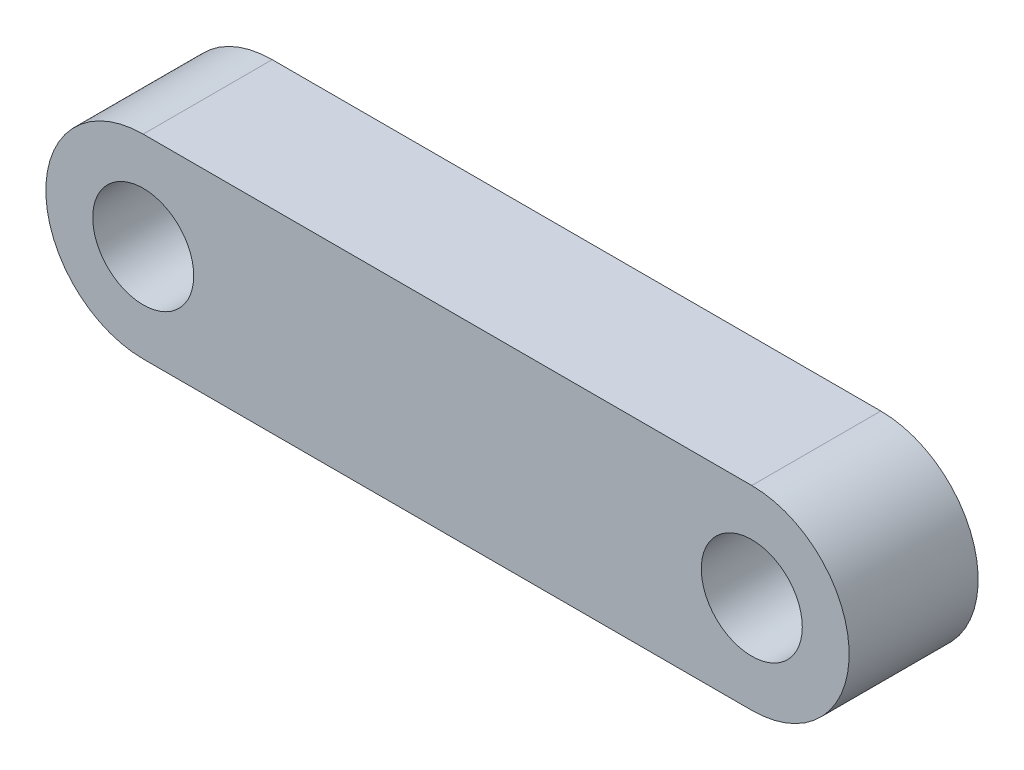
SolidWorks part; units mm, degrees
material "ABS"
ref_plane "Front Plane" through (0, 0, 0) normal (0, 0, 1) x (1, 0, 0)
ref_plane "Top Plane" through (0, 0, 0) normal (0, 1, 0) x (1, 0, 0)
ref_plane "Right Plane" through (0, 0, 0) normal (1, 0, 0) x (0, 0, -1)
sketch "Sketch1" plane through (0, 0, 0) normal (0, 0, 1) x (1, 0, 0)
  line L0 (0, 27.2364) -> (0, -32.7408) construction
  line L1 (25, -36.3) -> (-25, -36.3)
  line L2 (-30.9956, -23.0035) -> (-5.9956, 5.2965)
  line L3 (30.9956, -23.0035) -> (5.9956, 5.2965)
  line L4 (-25, -20.3) -> (25, -20.3)
  circle A0 centre (0, 0) radius 4
  circle A1 centre (0, 0) radius 11 construction
  circle A2 centre (-25, -28.3) radius 4.15
  arc A3 (-25, -36.3) -> (-30.9956, -23.0035) centre (-25, -28.3) cw
  arc A4 (-5.9956, 5.2965) -> (5.9956, 5.2965) centre (0, 0) cw
  arc A5 (25, -36.3) -> (30.9956, -23.0035) centre (25, -28.3) ccw
  circle A6 centre (25, -28.3) radius 4.15
  arc A7 (-25, -20.3) -> (-30.9956, -23.0035) centre (-25, -28.3) ccw
  arc A8 (25, -20.3) -> (30.9956, -23.0035) centre (25, -28.3) cw
  point P8 (0, 11)
  point P15 (0, -36.3)
  point P21 (0, -20.3)
  dimension "D1" = 8
  dimension "D2" = 22
  dimension "D3" = 8.3
  dimension "D6" = 8
  dimension "D7" = 8
  dimension "D4" = 25
  dimension "D5" = 39.3
extrude "Boss-Extrude2" add sketch "Sketch1" against normal blind 10.6 contours L0 L4 A7 A3 L1 A2 | L4 L0 L1 A5 A8 A6
equation "\"rod_diameter\"= 8"
equation "\"rod_hole_thickness\"= 4"
equation "\"rod_radius\"= \"rod_diameter\" / 2"
equation "\"platter_diameter\"= 320"
equation "\"platter_radius\"= \"platter_diameter\" / 2"
equation "\"extruder_mount_hole_spacing\"= 75"
equation "\"arm_rod_spacing\"= 40"
equation "\"motor_level_rod_spacing\"= 15"
equation "\"linear_bearing_diameter\"= 15"
equation "\"z_rod_spacing\"= 75"
equation "\"platter_rod_spacing\"= 50"
equation "\"rod_nut_thickness\"= 6.5"
equation "\"rod_nut_inscribed_diameter\"= 13"
equation "\"z_height\"= 400"
equation "\"D1@Sketch1\"=\"rod_diameter\""
equation "\"D3@Sketch1\"=\"rod_diameter\"+\"printed_hole_tolerance\""
equation "\"D4@Sketch1\"=\"platter_rod_spacing\"/2"
equation "\"D6@Sketch1\"=\"rod_radius\"+\"rod_hole_thickness\""
equation "\"D7@Sketch1\"=\"rod_radius\"+\"rod_hole_thickness\""
equation "\"top_frame_spacing\"= 100"
equation "\"z_drive_rod_offset\"= 12"
equation "\"gear_pitch\"=2"
equation "\"r_gear_teeth\"= 450"
equation "\"theta_gear_teeth\"= 385"
equation "\"sheet_thickness\"=5.333"
equation "\"sheet_tab_hole_thickness\"= \"sheet_thickness\""
equation "\"sheet_tab_width\"= \"sheet_thickness\"*2"
equation "\"sheet_double_tab_width\"= 35"
equation "\"sheet_bolt_diameter\"= 3"
equation "\"sheet_bolt_length\"= 16"
equation "\"sheet_nut_diameter\"= 5.5"
equation "\"sheet_nut_thickness\"= 2.5"
equation "\"sheet_nut_depth\"= 10"
equation "\"bearing_outside_diameter\"= 22"
equation "\"bearing_thickness\"= 7"
equation "\"corner_part_thickness\"= \"sheet_thickness\" + \"bearing_thickness\""
equation "\"setscrew_nut_diameter\"= 6"
equation "\"setscrew_nut_thickness\"= 3"
equation "\"setscrew_bolt_diameter\"= 3"
equation "\"motor_shaft_diameter\"= 5.7"
equation "\"printed_hole_tolerance\"= 0.3"
